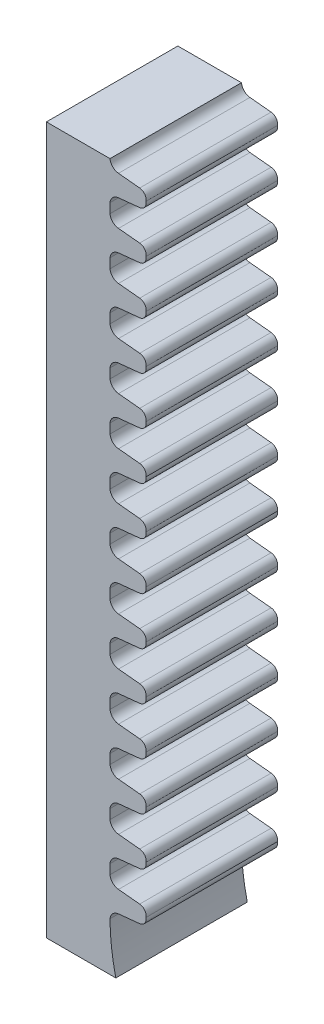
SolidWorks part; units mm, degrees
ref_plane "Front Plane" through (0, 0, 0) normal (0, 0, 1) x (1, 0, 0)
ref_plane "Top Plane" through (0, 0, 0) normal (0, 1, 0) x (1, 0, 0)
ref_plane "Right Plane" through (0, 0, 0) normal (1, 0, 0) x (0, 0, -1)
sketch "Sketch1" plane through (0, 0, 0) normal (0, 0, 1) x (1, 0, 0)
  line L1 (-28, 0) -> (0, 0)
  line L6 (-17.1, 20) -> (-17.1, 51)
  line L7 (-17.1, 51) -> (-20.1, 51)
  line L9 (0, 10) -> (-7.1, 10)
  line L11 (-20.1, 51) -> (-20.1, 6)
  line L12 (-28, 0) -> (-28, 50)
  line L13 (-28, 50) -> (-24, 50)
  line L14 (-24, 50) -> (-24, 6)
  line L15 (-24, 6) -> (-20.1, 6)
  line L16 (0, 10) -> (0, 0)
  arc A1 (-17.1, 20) -> (-7.1, 10) centre (-7.1, 20) ccw
  dimension "D8" = 10
  dimension "D1" = 45
  dimension "D2" = 3.9
  dimension "D3" = 3
  dimension "D4" = 4
  dimension "D5" = 50
  dimension "45" = 28
  dimension "D6" = 6
  dimension "D7" = 10
extrude "Boss-Extrude1" add sketch "Sketch1" along normal blind 6.2
sketch "Sketch7" plane through (0, 0, 6.2) normal (0, 0, 1) x (1, 0, 0)
  line L0 (-17.1, 20) -> (-17.1, 51) construction
  line L1 (-15.4, 50.1) -> (-17.4129, 50.1) construction
  line L2 (-16.7, 50.6) -> (-15.7, 50.5)
  line L3 (-16.7, 49.6) -> (-15.7, 49.7)
  line L4 (-17.1, 49.2) -> (-17.1, 48.75)
  line L5 (-16.7, 48.35) -> (-15.7, 48.25)
  line L6 (-16.7, 47.35) -> (-15.7, 47.45)
  line L7 (-16.7, 46.1) -> (-15.7, 46)
  line L8 (-16.7, 45.1) -> (-15.7, 45.2)
  line L9 (-16.7, 43.85) -> (-15.7, 43.75)
  line L10 (-16.7, 42.85) -> (-15.7, 42.95)
  line L11 (-16.7, 41.6) -> (-15.7, 41.5)
  line L12 (-16.7, 40.6) -> (-15.7, 40.7)
  line L13 (-16.7, 39.35) -> (-15.7, 39.25)
  line L14 (-16.7, 38.35) -> (-15.7, 38.45)
  line L15 (-16.7, 37.1) -> (-15.7, 37)
  line L16 (-16.7, 36.1) -> (-15.7, 36.2)
  line L17 (-16.7, 34.85) -> (-15.7, 34.75)
  line L18 (-16.7, 33.85) -> (-15.7, 33.95)
  line L19 (-16.7, 32.6) -> (-15.7, 32.5)
  line L20 (-16.7, 31.6) -> (-15.7, 31.7)
  line L21 (-16.7, 30.35) -> (-15.7, 30.25)
  line L22 (-16.7, 29.35) -> (-15.7, 29.45)
  line L23 (-16.7, 28.1) -> (-15.7, 28)
  line L24 (-16.7, 27.1) -> (-15.7, 27.2)
  line L25 (-16.7, 25.85) -> (-15.7, 25.75)
  line L26 (-16.7, 24.85) -> (-15.7, 24.95)
  line L27 (-16.7, 23.6) -> (-15.7, 23.5)
  line L28 (-16.7, 22.6) -> (-15.7, 22.7)
  line L29 (-16.7, 21.35) -> (-15.7, 21.25)
  line L30 (-16.7, 20.35) -> (-15.7, 20.45)
  line L31 (-17.1, 19.95) -> (-17.9565, 50.55)
  line L32 (-17.9565, 50.55) -> (-17.1, 51)
  line L33 (-17.1, 46.95) -> (-17.1, 46.5)
  line L34 (-17.1, 44.7) -> (-17.1, 44.25)
  line L35 (-17.1, 42.45) -> (-17.1, 42)
  line L36 (-17.1, 40.2) -> (-17.1, 39.75)
  line L37 (-17.1, 37.95) -> (-17.1, 37.5)
  line L38 (-17.1, 35.7) -> (-17.1, 35.25)
  line L39 (-17.1, 33.45) -> (-17.1, 33)
  line L40 (-17.1, 31.2) -> (-17.1, 30.75)
  line L41 (-17.1, 28.95) -> (-17.1, 28.5)
  line L42 (-17.1, 26.7) -> (-17.1, 26.25)
  line L43 (-17.1, 24.45) -> (-17.1, 24)
  line L44 (-17.1, 22.2) -> (-17.1, 21.75)
  arc A0 (-17.1, 51) -> (-16.7, 50.6) centre (-16.6556, 51.0444) ccw
  arc A1 (-15.7, 50.5) -> (-15.4, 50.1) centre (-15.7338, 50.1622) cw
  arc A2 (-17.1, 49.2) -> (-16.7, 49.6) centre (-16.6556, 49.1556) cw
  arc A3 (-15.7, 49.7) -> (-15.4, 50.1) centre (-15.7338, 50.0378) ccw
  arc A4 (-17.1, 48.75) -> (-16.7, 48.35) centre (-16.6556, 48.7944) ccw
  arc A5 (-15.7, 48.25) -> (-15.4, 47.85) centre (-15.7338, 47.9122) cw
  arc A6 (-15.7, 47.45) -> (-15.4, 47.85) centre (-15.7338, 47.7878) ccw
  arc A7 (-17.1, 46.95) -> (-16.7, 47.35) centre (-16.6556, 46.9056) cw
  arc A8 (-17.1, 46.5) -> (-16.7, 46.1) centre (-16.6556, 46.5444) ccw
  arc A9 (-15.7, 46) -> (-15.4, 45.6) centre (-15.7338, 45.6622) cw
  arc A10 (-15.7, 45.2) -> (-15.4, 45.6) centre (-15.7338, 45.5378) ccw
  arc A11 (-17.1, 44.7) -> (-16.7, 45.1) centre (-16.6556, 44.6556) cw
  arc A12 (-17.1, 44.25) -> (-16.7, 43.85) centre (-16.6556, 44.2944) ccw
  arc A13 (-15.7, 43.75) -> (-15.4, 43.35) centre (-15.7338, 43.4122) cw
  arc A14 (-15.7, 42.95) -> (-15.4, 43.35) centre (-15.7338, 43.2878) ccw
  arc A15 (-17.1, 42.45) -> (-16.7, 42.85) centre (-16.6556, 42.4056) cw
  arc A16 (-17.1, 42) -> (-16.7, 41.6) centre (-16.6556, 42.0444) ccw
  arc A17 (-15.7, 41.5) -> (-15.4, 41.1) centre (-15.7338, 41.1622) cw
  arc A18 (-15.7, 40.7) -> (-15.4, 41.1) centre (-15.7338, 41.0378) ccw
  arc A19 (-17.1, 40.2) -> (-16.7, 40.6) centre (-16.6556, 40.1556) cw
  arc A20 (-17.1, 39.75) -> (-16.7, 39.35) centre (-16.6556, 39.7944) ccw
  arc A21 (-15.7, 39.25) -> (-15.4, 38.85) centre (-15.7338, 38.9122) cw
  arc A22 (-15.7, 38.45) -> (-15.4, 38.85) centre (-15.7338, 38.7878) ccw
  arc A23 (-17.1, 37.95) -> (-16.7, 38.35) centre (-16.6556, 37.9056) cw
  arc A24 (-17.1, 37.5) -> (-16.7, 37.1) centre (-16.6556, 37.5444) ccw
  arc A25 (-15.7, 37) -> (-15.4, 36.6) centre (-15.7338, 36.6622) cw
  arc A26 (-15.7, 36.2) -> (-15.4, 36.6) centre (-15.7338, 36.5378) ccw
  arc A27 (-17.1, 35.7) -> (-16.7, 36.1) centre (-16.6556, 35.6556) cw
  arc A28 (-17.1, 35.25) -> (-16.7, 34.85) centre (-16.6556, 35.2944) ccw
  arc A29 (-15.7, 34.75) -> (-15.4, 34.35) centre (-15.7338, 34.4122) cw
  arc A30 (-15.7, 33.95) -> (-15.4, 34.35) centre (-15.7338, 34.2878) ccw
  arc A31 (-17.1, 33.45) -> (-16.7, 33.85) centre (-16.6556, 33.4056) cw
  arc A32 (-17.1, 33) -> (-16.7, 32.6) centre (-16.6556, 33.0444) ccw
  arc A33 (-15.7, 32.5) -> (-15.4, 32.1) centre (-15.7338, 32.1622) cw
  arc A34 (-15.7, 31.7) -> (-15.4, 32.1) centre (-15.7338, 32.0378) ccw
  arc A35 (-17.1, 31.2) -> (-16.7, 31.6) centre (-16.6556, 31.1556) cw
  arc A36 (-17.1, 30.75) -> (-16.7, 30.35) centre (-16.6556, 30.7944) ccw
  arc A37 (-15.7, 30.25) -> (-15.4, 29.85) centre (-15.7338, 29.9122) cw
  arc A38 (-15.7, 29.45) -> (-15.4, 29.85) centre (-15.7338, 29.7878) ccw
  arc A39 (-17.1, 28.95) -> (-16.7, 29.35) centre (-16.6556, 28.9056) cw
  arc A40 (-17.1, 28.5) -> (-16.7, 28.1) centre (-16.6556, 28.5444) ccw
  arc A41 (-15.7, 28) -> (-15.4, 27.6) centre (-15.7338, 27.6622) cw
  arc A42 (-15.7, 27.2) -> (-15.4, 27.6) centre (-15.7338, 27.5378) ccw
  arc A43 (-17.1, 26.7) -> (-16.7, 27.1) centre (-16.6556, 26.6556) cw
  arc A44 (-17.1, 26.25) -> (-16.7, 25.85) centre (-16.6556, 26.2944) ccw
  arc A45 (-15.7, 25.75) -> (-15.4, 25.35) centre (-15.7338, 25.4122) cw
  arc A46 (-15.7, 24.95) -> (-15.4, 25.35) centre (-15.7338, 25.2878) ccw
  arc A47 (-17.1, 24.45) -> (-16.7, 24.85) centre (-16.6556, 24.4056) cw
  arc A48 (-17.1, 24) -> (-16.7, 23.6) centre (-16.6556, 24.0444) ccw
  arc A49 (-15.7, 23.5) -> (-15.4, 23.1) centre (-15.7338, 23.1622) cw
  arc A50 (-15.7, 22.7) -> (-15.4, 23.1) centre (-15.7338, 23.0378) ccw
  arc A51 (-17.1, 22.2) -> (-16.7, 22.6) centre (-16.6556, 22.1556) cw
  arc A52 (-17.1, 21.75) -> (-16.7, 21.35) centre (-16.6556, 21.7944) ccw
  arc A53 (-15.7, 21.25) -> (-15.4, 20.85) centre (-15.7338, 20.9122) cw
  arc A54 (-15.7, 20.45) -> (-15.4, 20.85) centre (-15.7338, 20.7878) ccw
  arc A55 (-17.1, 19.95) -> (-16.7, 20.35) centre (-16.6556, 19.9056) cw
  dimension "D1" = 0.4
  dimension "D6" = 0.4
  dimension "D2" = 0.3
  dimension "D3" = 0.4
  dimension "D4" = 0.1
  dimension "D5" = 1
  dimension "D7" = 14
extrude "Boss-Extrude3" add sketch "Sketch7" against normal up to surface (6.2 mm away) up to face at (-17.0519, 22.9026, 0)
sketch "Sketch9" plane through (0, 0, 6.2) normal (0, 0, 1) x (1, 0, 0)
  line L1 (-29.231, 51.7369) -> (-20.8042, 51.7369)
  line L2 (-29.231, 51.7369) -> (-29.231, -2.081)
  line L3 (-29.231, -2.081) -> (-20.8042, -2.081)
  line L4 (-20.8042, 51.7369) -> (-20.8042, -2.081)
extrude "Cut-Extrude5" cut sketch "Sketch9" against normal through all both and the other way through all
sketch "Sketch10" plane through (0, 0, 6.2) normal (0, 0, 1) x (1, 0, 0)
  line L1 (-29.7173, 17.6677) -> (11.538, 17.6677)
  line L2 (-29.7173, 17.6677) -> (-29.7173, -1.4607)
  line L3 (-29.7173, -1.4607) -> (11.538, -1.4607)
  line L4 (11.538, 17.6677) -> (11.538, -1.4607)
extrude "Cut-Extrude6" cut sketch "Sketch10" against normal through all both and the other way through all
equation "\"D4@Sketch8\"=\"D2@Sketch8\"/2"
